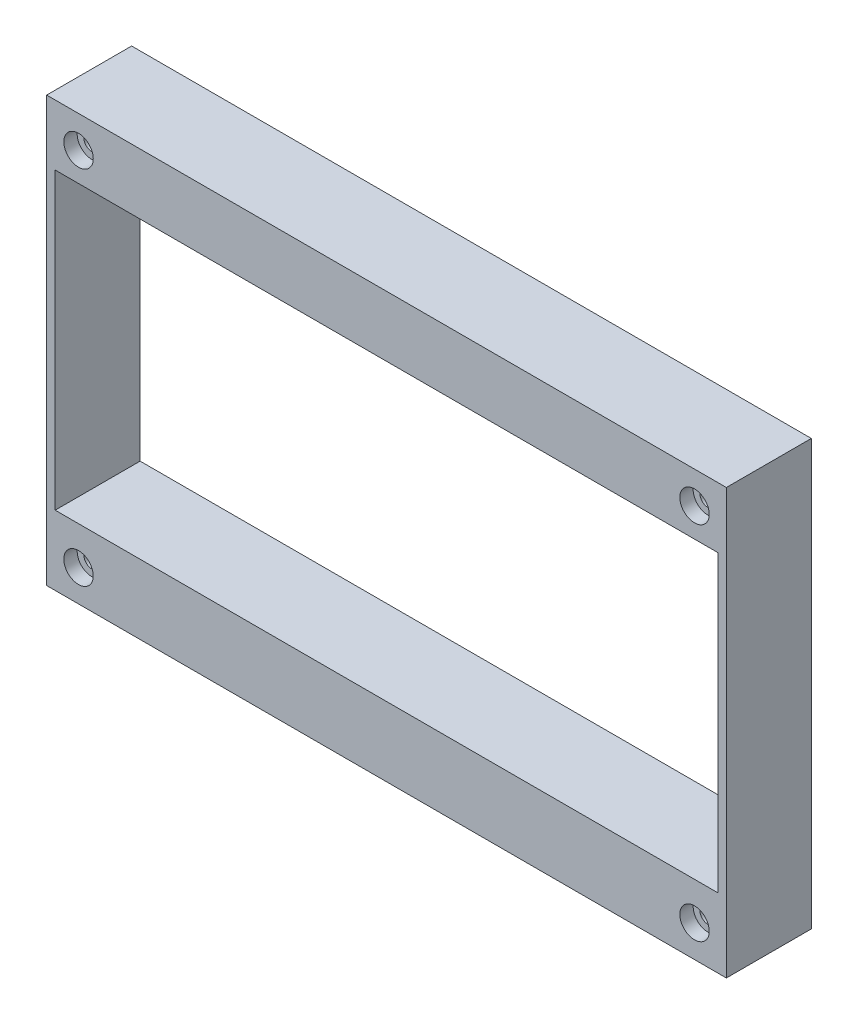
SolidWorks part; units mm, degrees
ref_plane "Front Plane" through (0, 0, 0) normal (0, 0, 1) x (1, 0, 0)
ref_plane "Top Plane" through (0, 0, 0) normal (0, 1, 0) x (1, 0, 0)
ref_plane "Right Plane" through (0, 0, 0) normal (1, 0, 0) x (0, 0, -1)
sketch "Sketch1" plane through (0, 0, 0) normal (0, 0, 1) x (1, 0, 0)
  line L1 (0, 0) -> (101.6, 0)
  line L2 (0, 0) -> (0, 63.5)
  line L3 (0, 63.5) -> (101.6, 63.5)
  line L4 (101.6, 0) -> (101.6, 63.5)
  dimension "D1" = 101.6
  dimension "D2" = 63.5
extrude "Boss-Extrude1" add sketch "Sketch1" along normal blind 12.7 contours L2 L1 L4 L3
sketch "Sketch2" plane through (0, 0, 12.7) normal (0, 0, 1) x (1, 0, 0)
  line L0 (0, 0) -> (0, 63.5) construction
  line L1 (1.27, 54.4314) -> (100.33, 54.4314)
  line L2 (1.27, 54.4314) -> (1.27, 10.3955)
  line L3 (1.27, 10.3955) -> (100.33, 10.3955)
  line L4 (100.33, 54.4314) -> (100.33, 10.3955)
  dimension "D1" = 99.06
  dimension "D2" = 1.27
extrude "Cut-Extrude1" cut sketch "Sketch2" against normal blind 12.7
sketch "Sketch3" plane through (0, 0, 0) normal (0, 0, -1) x (-1, 0, 0)
  line L0 (-101.6, 0) -> (-101.6, 63.5) construction
  line L1 (0, 0) -> (-101.6, 0) construction
  line L2 (0, 63.5) -> (-101.6, 63.5) construction
  circle A0 centre (-96.8375, 4.7625) radius 1.5875
  circle A1 centre (-96.8375, 58.7375) radius 1.5875
  circle A2 centre (-4.7625, 58.7375) radius 1.5875
  circle A3 centre (-4.7625, 4.7625) radius 1.5875
  point P14 (0, 0)
  point P15 (0, 0)
  point P16 (0, 0)
  dimension "D1" = 4.7625
  dimension "D2" = 4.7625
  dimension "D3" = 4.7625
  dimension "D4" = 4.7625
  dimension "D6" = 92.075
  dimension "D7" = 3.175
  dimension "D8" = 3.175
  dimension "D9" = 3.175
  dimension "D10" = 3.175
  dimension "D11" = 4.7625
  dimension "D12" = 4.7625
  dimension "D5" = 92.075
extrude "Cut-Extrude2" cut sketch "Sketch3" against normal blind 3.175
hole_wizard "CBORE for M2 SHCS1" positions "Sketch4" profile "Sketch5" counterbore size "M2" standard "ANSI Metric" end condition through all
sketch "Sketch4" plane through (0, 0, 12.7) normal (0, 0, 1) x (1, 0, 0)
  line L0 (101.6, 0) -> (101.6, 63.5) construction
  line L1 (0, 63.5) -> (101.6, 63.5) construction
  line L2 (0, 0) -> (101.6, 0) construction
  point P0 (96.8375, 4.7625)
  point P2 (96.8375, 58.7375)
  point P4 (4.7625, 58.7375)
  point P6 (4.7625, 4.7168)
  point P15 (0, 0)
  point P16 (0, 0)
  dimension "D1" = 4.7625
  dimension "D2" = 4.7625
  dimension "D3" = 4.7625
  dimension "D4" = 4.7625
  dimension "D5" = 92.075
  dimension "D6" = 92.075
  dimension "D7" = 4.7625
  dimension "D8" = 4.7168
sketch "Sketch5" plane through (96.8375, 4.7625, 12.7) normal (1, 0, 0) x (0, -1, 0)
  line L0 (0, 0) -> (0, 12.7)
  line L1 (0, 12.7) -> (1.2, 12.7)
  line L3 (1.2, 12.7) -> (1.2, 2)
  line L4 (1.2, 2) -> (2.2, 2)
  line L5 (2.2, 2) -> (2.2, 0)
  line L7 (2.2, 0) -> (0, 0)
  line L11 (0, -6.35) -> (0, 107.95) construction
  dimension "Thru Hole Dia." = 2.4
  dimension "Thru Hole Depth" = 12.7
  dimension "C'Bore Dia." = 4.4
  dimension "C'Bore Depth" = 2
